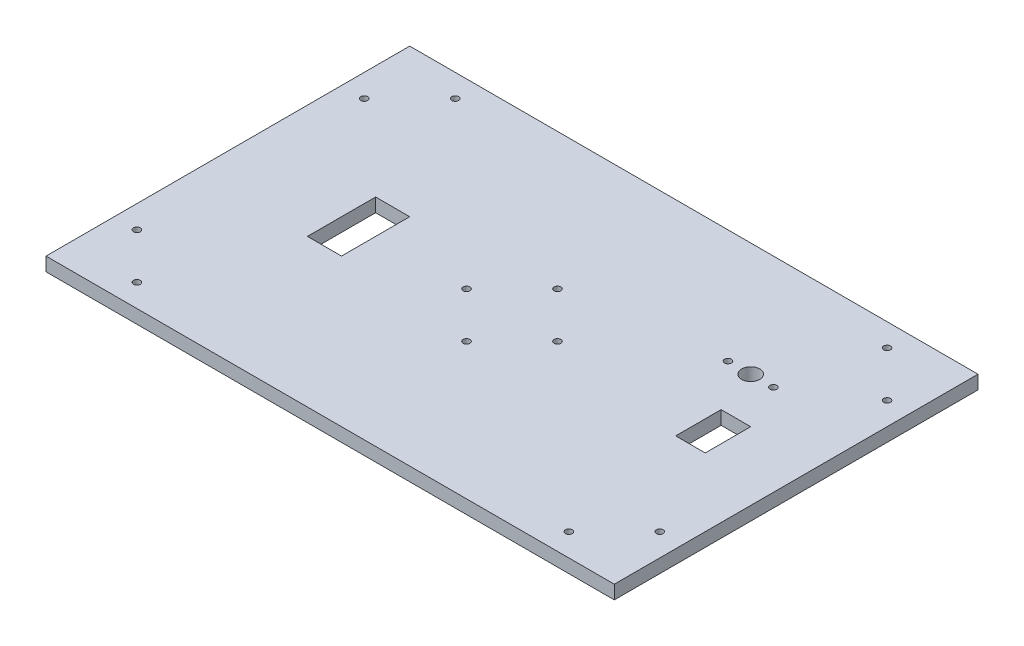
SolidWorks part; units mm, degrees
ref_plane "Спереди" through (0, 0, 0) normal (0, 0, 1) x (1, 0, 0)
ref_plane "Сверху" through (0, 0, 0) normal (0, 1, 0) x (1, 0, 0)
ref_plane "Справа" through (0, 0, 0) normal (1, 0, 0) x (0, 0, -1)
sketch "Эскиз1" plane through (0, 0, 0) normal (0, 1, 0) x (1, 0, 0)
  line L1 (-69.703, -78.9439) -> (180.297, -78.9439)
  line L2 (-69.703, -78.9439) -> (-69.703, 81.0561)
  line L3 (-69.703, 81.0561) -> (180.297, 81.0561)
  line L4 (180.297, -78.9439) -> (180.297, 81.0561)
  dimension "D1" = 160
  dimension "D2" = 250
extrude "Бобышка-Вытянуть1" add sketch "Эскиз1" along normal blind 6 contours L2 L3 L4 L1
sketch "Эскиз2" plane through (0, 6, 0) normal (0, 1, 0) x (1, 0, 0)
  line L0 (55.297, 81.0561) -> (55.297, -78.9439) construction
  line L1 (-69.703, 81.0561) -> (180.297, 81.0561) construction
  line L2 (-69.703, -78.9439) -> (180.297, -78.9439) construction
  line L3 (-69.703, 1.0561) -> (180.297, 1.0561) construction
  line L4 (-69.703, -78.9439) -> (-69.703, 81.0561) construction
  line L5 (180.297, -78.9439) -> (180.297, 81.0561) construction
  line L7 (-39.703, 71.0561) -> (-59.703, 51.0561) construction
  line L9 (-59.703, -48.9439) -> (-39.703, -68.9439) construction
  line L11 (150.297, 71.0561) -> (170.297, 51.0561) construction
  line L12 (170.297, -48.9439) -> (150.297, -68.9439) construction
  line L14 (-69.703, 81.0561) -> (-49.703, 61.0561) construction
  circle A0 centre (-39.703, 71.0561) radius 1.5
  circle A1 centre (-59.703, 51.0561) radius 1.5
  circle A2 centre (150.297, 71.0561) radius 1.5
  circle A3 centre (170.297, 51.0561) radius 1.5
  circle A4 centre (170.297, -48.9439) radius 1.5
  circle A5 centre (150.297, -68.9439) radius 1.5
  circle A6 centre (-59.703, -48.9439) radius 1.5
  circle A7 centre (-39.703, -68.9439) radius 1.5
  circle A8 centre (35.297, 1.0561) radius 1.5
  circle A9 centre (55.297, 21.0561) radius 1.5
  circle A10 centre (55.297, -18.9439) radius 1.5
  circle A11 centre (75.297, 1.0561) radius 1.5
  dimension "D5" = 3
  dimension "D6" = 20
  dimension "D8" = 3
  dimension "D9" = 20
  dimension "D7" = 20
  dimension "D1" = 45
  dimension "D2" = 28.2843
  dimension "D3" = 28.2843
  dimension "D4" = 20
  dimension "D10" = 20
extrude "Вырез-Вытянуть1" cut sketch "Эскиз2" against normal blind 6
sketch "Эскиз3" plane through (0, 6, 0) normal (0, 1, 0) x (1, 0, 0)
  line L0 (180.297, -78.9439) -> (180.297, 81.0561) construction
  line L1 (137.297, 11.0561) -> (150.297, 11.0561)
  line L2 (137.297, 11.0561) -> (137.297, -8.9439)
  line L3 (137.297, -8.9439) -> (150.297, -8.9439)
  line L4 (150.297, 11.0561) -> (150.297, -8.9439)
  line L6 (120.297, 31.0561) -> (140.297, 31.0561) construction
  line L7 (-69.703, 81.0561) -> (180.297, 81.0561) construction
  circle A0 centre (140.297, 31.0561) radius 1.5
  circle A1 centre (120.297, 31.0561) radius 1.5
  circle A2 centre (130.297, 31.0561) radius 4
  dimension "D5" = 3
  dimension "D6" = 3
  dimension "D8" = 8
  dimension "D1" = 20
  dimension "D2" = 13
  dimension "D3" = 30
  dimension "D4" = 70
  dimension "D7" = 20
  dimension "D9" = 50
  dimension "D10" = 50
extrude "Вырез-Вытянуть2" cut sketch "Эскиз3" against normal blind 6
sketch "Эскиз4" plane through (0, 6, 0) normal (0, 1, 0) x (1, 0, 0)
  line L0 (180.297, 1.0561) -> (-69.703, 1.0561) construction
  line L1 (-19.703, 16.0561) -> (-4.703, 16.0561)
  line L2 (-19.703, 16.0561) -> (-19.703, -13.9439)
  line L3 (-19.703, -13.9439) -> (-4.703, -13.9439)
  line L4 (-4.703, 16.0561) -> (-4.703, -13.9439)
  line L5 (180.297, -78.9439) -> (180.297, 81.0561) construction
  line L6 (-69.703, -78.9439) -> (-69.703, 81.0561) construction
  point P10 (-19.703, 1.0561)
  dimension "D1" = 0
  dimension "D2" = 15
  dimension "D3" = 30
  dimension "D4" = 50
extrude "Вырез-Вытянуть3" cut sketch "Эскиз4" against normal blind 6
